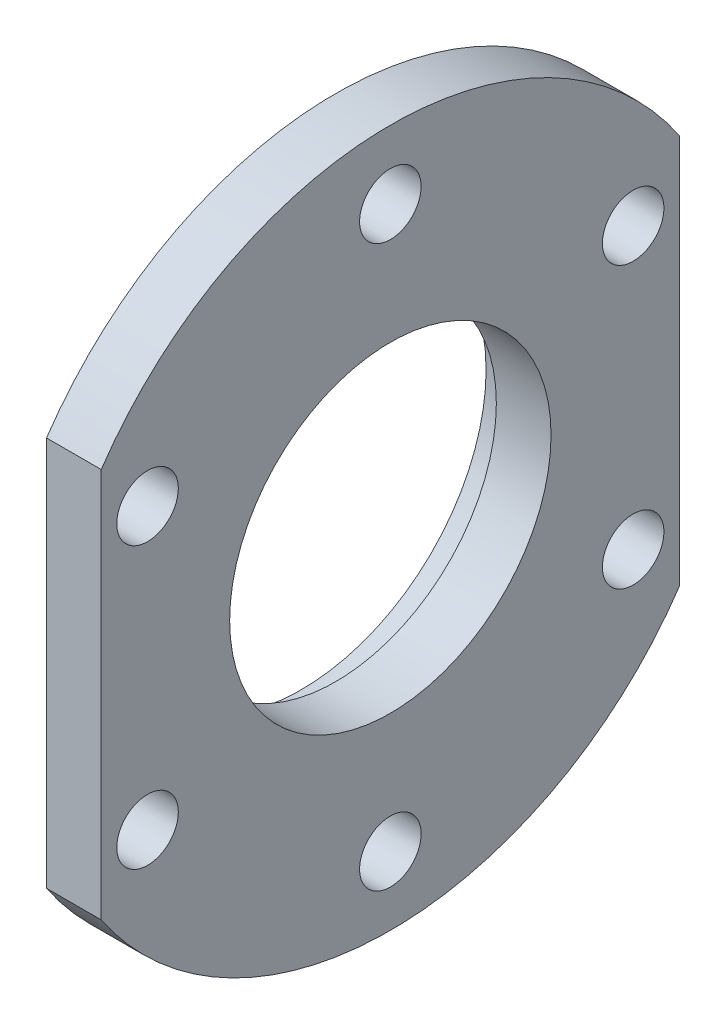
SolidWorks part; units mm, degrees
ref_plane "前视基准面" through (0, 0, 0) normal (0, 0, 1) x (1, 0, 0)
ref_plane "上视基准面" through (0, 0, 0) normal (0, 1, 0) x (1, 0, 0)
ref_plane "右视基准面" through (0, 0, 0) normal (1, 0, 0) x (0, 0, -1)
other "Configuration Table"
sketch "草图1" plane through (0, 0, 0) normal (1, 0, 0) x (0, 0, -1)
  line L0 (76.4053, 0) -> (-76.4053, 0) construction
  line L1 (0, 65.0015) -> (0, -65.0015) construction
  line L2 (0, 0) -> (42.2809, 28.5188) construction
  line L3 (42.2809, 28.5188) -> (42.2809, -28.5188)
  line L4 (-42.2809, 28.5188) -> (-42.2809, -28.5188)
  arc A0 (42.2809, 28.5188) -> (-42.2809, 28.5188) centre (0, 0) ccw
  circle A1 centre (0, 0) radius 23.5
  circle A3 centre (0, 41) radius 4.5
  circle A4 centre (35.507, 20.5) radius 4.5
  circle A5 centre (35.507, -20.5) radius 4.5
  circle A6 centre (0, -41) radius 4.5
  circle A7 centre (-35.507, -20.5) radius 4.5
  circle A8 centre (-35.507, 20.5) radius 4.5
  arc A9 (-42.2809, -28.5188) -> (42.2809, -28.5188) centre (0, 0) ccw
  point P8 (0, 0)
  point P11 (0, 0)
  point P26 (0, 0)
  dimension "D1" = 102
  dimension "D2" = 47
  dimension "D3" = 34
  dimension "D4" = 9
  dimension "D5" = 6
extrude "凸台-拉伸1" add sketch "草图1" along normal blind 8
sketch "草图2" plane through (0, 0, 0) normal (-1, 0, 0) x (0, 0, 1)
  circle A1 centre (0, 0) radius 31
extrude "凸台-拉伸2" add sketch "草图2" along normal blind 5
fillet "圆角1" radius 0.5 1 edges at (-5, 0, 31)
sketch "草图3" plane through (0, 0, 0) normal (1, 0, 0) x (0, 0, -1)
  circle A0 centre (0, 0) radius 27
extrude "切除-拉伸1" cut sketch "草图3" against normal through all
